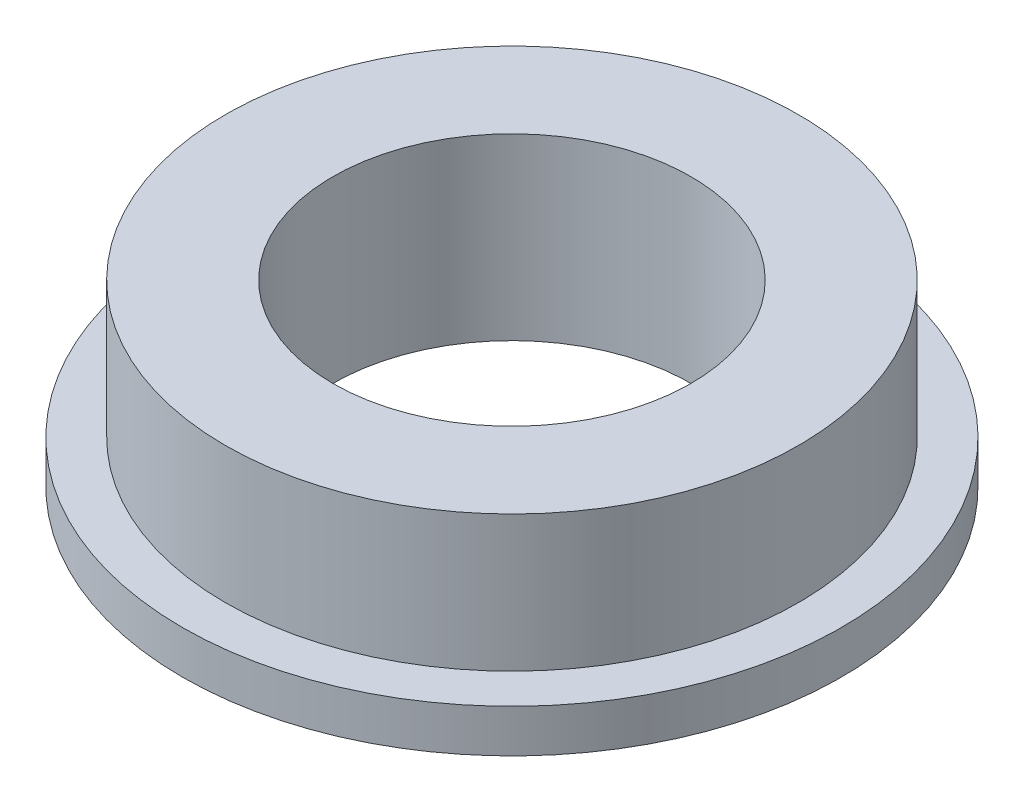
SolidWorks part; units mm, degrees
ref_plane "Front Plane" through (0, 0, 0) normal (0, 0, 1) x (1, 0, 0)
ref_plane "Top Plane" through (0, 0, 0) normal (0, 1, 0) x (1, 0, 0)
ref_plane "Right Plane" through (0, 0, 0) normal (1, 0, 0) x (0, 0, -1)
sketch "Sketch1" plane through (0, 0, 0) normal (0, 1, 0) x (1, 0, 0)
  circle A0 centre (0, 0) radius 4.6
  circle A1 centre (0, 0) radius 2.5
  dimension "D1" = 9.2
  dimension "D2" = 5
extrude "Boss-Extrude1" add sketch "Sketch1" along normal blind 0.6
sketch "Sketch2" plane through (0, 0, 0) normal (0, 1, 0) x (1, 0, 0)
  circle A0 centre (0, 0) radius 2.5
  circle A1 centre (0, 0) radius 4
  circle A2 centre (0, 0) radius 2.5 construction
  dimension "D1" = 8
extrude "Boss-Extrude2" add sketch "Sketch2" along normal blind 2.5
